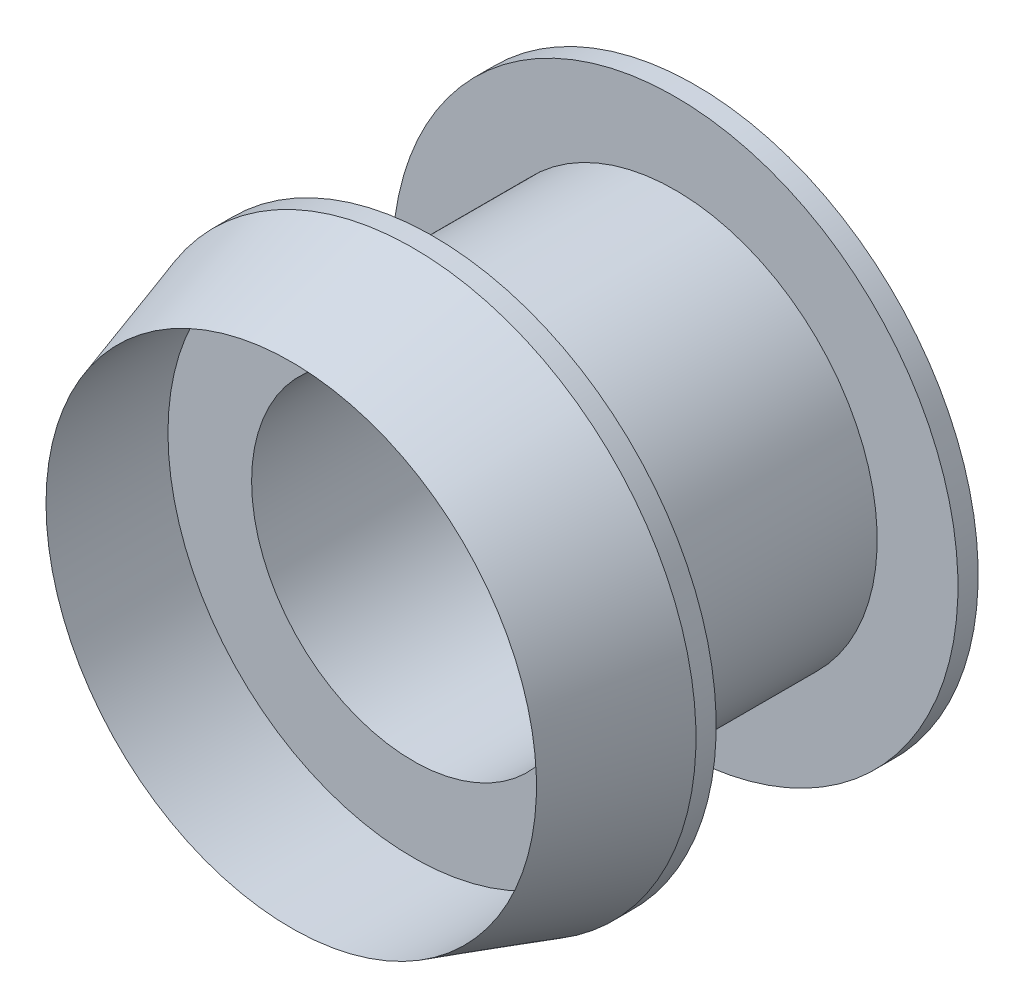
SolidWorks part; units mm, degrees
ref_plane "Front Plane" through (0, 0, 0) normal (1, 0, 0) x (0, 1, 0)
ref_plane "Top Plane" through (0, 0, 0) normal (0, 0, 1) x (0, 1, 0)
ref_plane "Right Plane" through (0, 0, 0) normal (0, 1, 0) x (-1, 0, 0)
sketch "Sketch1" plane through (0, 0, 0) normal (1, 0, 0) x (0, 1, 0)
  line L0 (-63.5, -0.8609) -> (-101.5958, -0.8609)
  line L6 (-63.5, -0.8609) -> (-63.5, 87.8471)
  line L7 (-12.7, 0) -> (-12.7, 100.9873) construction
  line L13 (-101.5958, -0.8609) -> (-101.5958, 5.4891)
  line L14 (-101.5958, 5.4891) -> (-76.2, 5.4891)
  line L15 (-76.2, 5.4891) -> (-76.2, 81.4971)
  line L16 (-76.2, 81.4971) -> (-101.5958, 81.4971)
  line L17 (-101.5958, 81.4971) -> (-101.5958, 87.8471)
  line L19 (-101.5958, 87.8471) -> (-89.7894, 126.186)
  line L21 (-63.5, 87.8471) -> (-89.7894, 87.8471)
  line L22 (-89.7894, 87.8471) -> (-89.7894, 126.186)
  point P3 (0, 0)
  point P14 (0, 0)
  dimension "D1" = 50.8
  dimension "D2" = 88.9
  dimension "D3" = 63.5
  dimension "D5" = 6.35
  dimension "D6" = 6.35
revolve "Revolve1" add sketch "Sketch1" angle 360 about L7
